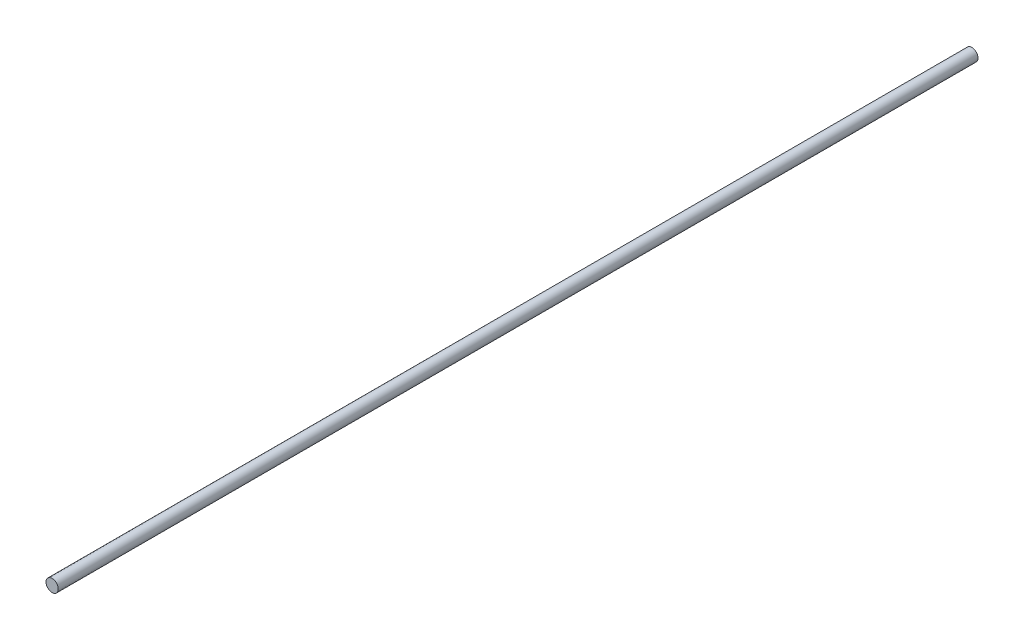
SolidWorks part; units mm, degrees
material "Zoltek Panex 33"
ref_plane "Front Plane" through (0, 0, 0) normal (0, 0, 1) x (1, 0, 0)
ref_plane "Top Plane" through (0, 0, 0) normal (0, 1, 0) x (1, 0, 0)
ref_plane "Right Plane" through (0, 0, 0) normal (1, 0, 0) x (0, 0, -1)
sketch "Sketch1" plane through (0, 0, 0) normal (0, 0, 1) x (1, 0, 0)
  circle A0 centre (0, 0) radius 2
extrude "Boss-Extrude1" add sketch "Sketch1" along normal blind 300
